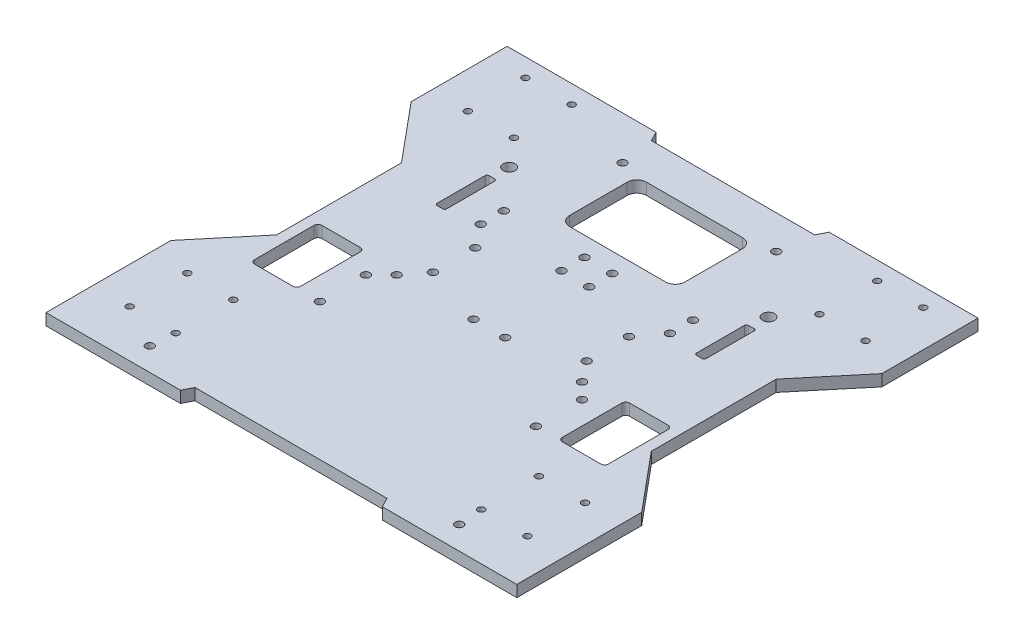
SolidWorks part; units mm, degrees
ref_plane "前视基准面" through (0, 0, 0) normal (0, 0, 1) x (1, 0, 0)
ref_plane "上视基准面" through (0, 0, 0) normal (0, 1, 0) x (1, 0, 0)
ref_plane "右视基准面" through (0, 0, 0) normal (1, 0, 0) x (0, 0, -1)
sketch "Sketch1" plane through (0, 0, 0) normal (0, 1, 0) x (1, 0, 0)
  line L0 (-122.5, 62.5) -> (-97.5, 32.5)
  line L1 (-122.5, 127.5) -> (-52.5, 127.5) construction
  line L2 (-122.5, 112.5) -> (-122.5, 62.5)
  line L3 (-122.5, -127.5) -> (-52.5, -127.5)
  line L4 (122.5, 112.5) -> (122.5, 62.5)
  line L5 (0, -127.5) -> (0, 127.5) construction
  line L6 (-122.5, 0) -> (122.5, 0) construction
  line L7 (-97.5, 32.5) -> (-97.5, -32.5)
  line L8 (-45, 112.5) -> (-42.5, 107.5)
  line L9 (-42.5, 107.5) -> (42.5, 107.5)
  line L10 (97.5, 32.5) -> (97.5, -32.5)
  line L11 (122.5, 62.5) -> (97.5, 32.5)
  line L12 (45, 112.5) -> (42.5, 107.5)
  line L13 (-122.5, -62.5) -> (-97.5, -32.5)
  line L14 (122.5, -62.5) -> (97.5, -32.5)
  line L15 (52.5, -127.5) -> (50, -122.5)
  line L16 (-42.5, -107.5) -> (0, -107.5) construction
  line L17 (-52.5, -127.5) -> (-50, -122.5)
  line L18 (-52.5, 127.5) -> (0, 127.5) construction
  line L19 (52.5, 127.5) -> (122.5, 127.5) construction
  line L20 (0, 127.5) -> (52.5, 127.5) construction
  line L21 (122.5, 62.5) -> (122.5, 0) construction
  line L22 (122.5, -62.5) -> (122.5, -127.5)
  line L23 (122.5, 0) -> (122.5, -62.5) construction
  line L24 (0, -127.5) -> (52.5, -127.5) construction
  line L25 (52.5, -127.5) -> (122.5, -127.5)
  line L26 (-52.5, -127.5) -> (0, -127.5) construction
  line L27 (-122.5, 62.5) -> (-122.5, 0) construction
  line L28 (-122.5, -62.5) -> (-122.5, -127.5)
  line L29 (-122.5, 0) -> (-122.5, -62.5) construction
  line L30 (0, -107.5) -> (42.5, -107.5) construction
  line L32 (50, -122.5) -> (-50, -122.5)
  line L37 (0, -60) -> (0, -40) construction
  line L38 (25, -50) -> (-25, -50) construction
  line L39 (50, -122.5) -> (42.5, -107.5) construction
  line L40 (-50, -122.5) -> (-42.5, -107.5) construction
  line L44 (122.5, 112.5) -> (45, 112.5)
  line L45 (122.5, 127.5) -> (122.5, 112.5) construction
  line L46 (52.5, 127.5) -> (45, 112.5) construction
  line L47 (45, 112.5) -> (0, 112.5) construction
  line L48 (-45, 112.5) -> (-122.5, 112.5)
  line L49 (0, 112.5) -> (-45, 112.5) construction
  line L50 (-122.5, 127.5) -> (-122.5, 112.5) construction
  line L51 (-52.5, 127.5) -> (-45, 112.5) construction
  point P0 (0, 0)
  point P15 (0, 107.5)
  point P17 (-97.5, 0)
  point P18 (97.5, 0)
  point P24 (0, -50)
  point P31 (-25, -60)
  point P37 (25, -40)
  point P40 (25, -60)
  dimension "D3" = 70
  dimension "D4" = 20
  dimension "D12" = 5
  dimension "D1" = 245
  dimension "D2" = 255
  dimension "D5" = 10
  dimension "D6" = 65
  dimension "D7" = 30
  dimension "D8" = 25
  dimension "D9" = 20
  dimension "D10" = 50
  dimension "D11" = 50
  dimension "D13" = 15
extrude "Boss-Extrude1" add sketch "Sketch1" along normal blind 6
sketch "Sketch4" plane through (0, 6, 0) normal (0, 1, 0) x (1, 0, 0)
  line L4 (-122.5, 112.5) -> (-122.5, 62.5) construction
  line B0 (-74.5, 108) -> (-108.5, 108)
  line B1 (-108.5, 108) -> (-108.5, 68)
  line B2 (-108.5, 68) -> (-74.5, 68)
  line B3 (-71.5, 71) -> (-71.5, 105)
  arc B4 (-71.5, 105) -> (-74.5, 108) centre (-74.5, 105) ccw
  arc B5 (-74.5, 68) -> (-71.5, 71) centre (-74.5, 71) ccw
  circle B6 centre (-103.5, 103) radius 1.75
  circle B7 centre (-103.5, 73) radius 1.75
  circle B8 centre (-79.5, 73) radius 1.75
  circle B9 centre (-79.5, 103) radius 1.75
  dimension "D1" = 14
  dimension "D2" = 5.5
sketch_block_instance "Block3-1"
sketch_block "Block3" parameters "D1"=3.5
extrude "Cut-Extrude3" cut sketch "Sketch4" against normal up to next contours B6 | B8 | B9 | B7
mirror "Mirror1" about plane through (0, 0, 0) normal (0, 0, 1) of "Cut-Extrude3"
mirror "Mirror2" about plane through (0, 0, 0) normal (1, 0, 0) of "Mirror1", "Cut-Extrude3"
sketch "Sketch14" plane through (0, 6, 0) normal (0, 1, 0) x (1, 0, 0)
  line L0 (-122.5, -62.5) -> (-122.5, -127.5) construction
  line L1 (122.5, -127.5) -> (122.5, -62.5) construction
  line L2 (-122.5, -127.5) -> (-52.5, -127.5) construction
  line L3 (52.5, -127.5) -> (122.5, -127.5) construction
  circle A1 centre (80.5, -115.5) radius 2.1
  circle A3 centre (-80.5, -115.5) radius 2.1
  dimension "D3" = 4.2
  dimension "D1" = 42
  dimension "D2" = 42
  dimension "D4" = 12
  dimension "D5" = 12
extrude "Cut-Extrude9" cut sketch "Sketch14" against normal up to next
sketch "Sketch16" plane through (0, 0, 0) normal (0, -1, 0) x (1, 0, 0)
  line L0 (40, -30) -> (40, -90) construction
  line L1 (40, -30) -> (-40, -30) construction
  line L2 (40, -30) -> (40, 30) construction
  line L3 (40, 30) -> (-40, 30) construction
  line L4 (-40, -30) -> (-40, 30) construction
  line L5 (0, 30) -> (0, -30) construction
  line L6 (40, 0) -> (-40, 0) construction
  line L7 (-40, -30) -> (-40, -90) construction
  circle A0 centre (40, 30) radius 2.1 construction
  circle A3 centre (40, -90) radius 2.1
  circle A4 centre (-40, -90) radius 2.1
  circle A11 centre (40, -13.3585) radius 2.1
  circle A12 centre (40, 8.6748) radius 2.1
  circle A13 centre (-40, 8.6748) radius 2.1
  circle A14 centre (-40, -13.3585) radius 2.1
  point P0 (0, 0)
  dimension "D4" = 4.2
  dimension "D1" = 60
  dimension "D2" = 80
  dimension "D3" = 60
extrude "Cut-Extrude12" cut sketch "Sketch16" against normal up to next
sketch "Sketch15" plane through (0, 6, 0) normal (0, 1, 0) x (1, 0, 0)
  line L8 (0, -2.75) -> (0, 2.75) construction
  line L9 (42.5, 107.5) -> (-42.5, 107.5) construction
  line L12 (-45, 112.5) -> (-122.5, 112.5) construction
  point P0 (-67.491, 22.5)
  point P30 (63.897, -115.6149)
  point P38 (63.897, -88.6149)
  line B0 (68.9826, 22.499) -> (65.9994, 22.501)
  line B1 (65, 23.501) -> (65, 48.501)
  line B2 (69.9994, 48.4984) -> (69.9832, 23.4984)
  line B3 (66.0006, 49.501) -> (69, 49.499)
  arc B4 (65.9994, 22.501) -> (65, 23.501) centre (66, 23.501) cw
  circle B5 centre (67.5058, 58.5) radius 3.1
  arc B6 (68.9826, 22.499) -> (69.9832, 23.4984) centre (68.9832, 23.499) ccw
  arc B7 (69, 49.499) -> (69.9994, 48.4984) centre (68.9994, 48.499) cw
  arc B8 (65, 48.501) -> (66.0006, 49.501) centre (66, 48.501) cw
  line B9 (-68.9826, 22.499) -> (-65.9994, 22.501)
  line B10 (-65, 23.501) -> (-65, 48.501)
  line B11 (-69.9994, 48.4984) -> (-69.9832, 23.4984)
  line B12 (-66.0006, 49.501) -> (-69, 49.499)
  arc B13 (-65.9994, 22.501) -> (-65, 23.501) centre (-66, 23.501) ccw
  circle B14 centre (-67.5058, 58.5) radius 3.1
  arc B15 (-68.9826, 22.499) -> (-69.9832, 23.4984) centre (-68.9832, 23.499) cw
  arc B16 (-69, 49.499) -> (-69.9994, 48.4984) centre (-68.9994, 48.499) ccw
  arc B17 (-65, 48.501) -> (-66.0006, 49.501) centre (-66, 48.501) ccw
  dimension "D2" = 90
  dimension "D1" = 130
sketch_block_instance "Block4-1"
sketch_block "Block4" parameters "D1"=1, "D2"=1, "D3"=5.1
sketch_block_instance "Block4-2"
extrude "Cut-Extrude11" cut sketch "Sketch15" against normal up to next
sketch "Sketch19" plane through (0, 6, 0) normal (0, 1, 0) x (1, 0, 0)
  circle A8 centre (-49.2275, 25.4525) radius 2.1
  circle A9 centre (-49.2275, 37.4525) radius 2.1
  circle A10 centre (-7.2275, 37.4525) radius 2.1
  circle A11 centre (-7.2275, 25.4525) radius 2.1
  circle A12 centre (7.2275, 25.4525) radius 2.1
  circle A13 centre (7.2275, 37.4525) radius 2.1
  circle A14 centre (49.2275, 37.4525) radius 2.1
  circle A15 centre (49.2275, 25.4525) radius 2.1
  dimension "D1" = 4.2
extrude "Cut-Extrude14" cut sketch "Sketch19" against normal up to next
sketch "Sketch20" plane through (0, 6, 0) normal (0, 1, 0) x (1, 0, 0)
  line L0 (0, -2.75) -> (0, 2.75) construction
  circle A4 centre (-56.2275, -51.3) radius 2.1
  circle A5 centre (-56.2275, -27.3) radius 2.1
  circle A6 centre (-48.2275, -19.3) radius 2.1
  circle A7 centre (-8.2275, -19.3) radius 2.1
  circle A8 centre (8.2275, -19.3) radius 2.1
  circle A9 centre (48.2275, -19.3) radius 2.1
  circle A10 centre (56.2275, -27.3) radius 2.1
  circle A11 centre (56.2275, -51.3) radius 2.1
  dimension "D1" = 4.2
extrude "Cut-Extrude15" cut sketch "Sketch20" against normal up to next
sketch "Sketch17" plane through (0, 6, 0) normal (0, 1, 0) x (1, 0, 0)
  line L0 (-0.0428, 10.3282) -> (-0.0428, 91.3341) construction
  line L1 (42.5, 107.5) -> (-42.5, 107.5) construction
  line L2 (-25.0428, 87.5) -> (24.9572, 87.5)
  line L3 (-30.0428, 82.5) -> (-30.0428, 52.5)
  line L4 (-25.0428, 47.5) -> (24.9572, 47.5)
  line L5 (29.9572, 82.5) -> (29.9572, 52.5)
  line L6 (-0.0428, 2.8282) -> (-0.0428, 87.5) construction
  line L7 (-30.0428, 67.5) -> (29.9572, 67.5) construction
  line L8 (0, -2.75) -> (0, 2.75) construction
  line L9 (-90.0796, -16.4007) -> (-70.0796, -16.4007)
  line L10 (-92.0796, -18.4007) -> (-92.0796, -49.4007)
  line L11 (-90.0796, -51.4007) -> (-70.0796, -51.4007)
  line L12 (-68.0796, -18.4007) -> (-68.0796, -49.4007)
  line L13 (68.0796, -18.4007) -> (68.0796, -49.4007)
  line L14 (90.0796, -51.4007) -> (70.0796, -51.4007)
  line L15 (92.0796, -18.4007) -> (92.0796, -49.4007)
  line L16 (90.0796, -16.4007) -> (70.0796, -16.4007)
  arc A0 (-25.0428, 87.5) -> (-30.0428, 82.5) centre (-25.0428, 82.5) ccw
  arc A1 (-30.0428, 52.5) -> (-25.0428, 47.5) centre (-25.0428, 52.5) ccw
  arc A2 (24.9572, 47.5) -> (29.9572, 52.5) centre (24.9572, 52.5) ccw
  arc A3 (24.9572, 87.5) -> (29.9572, 82.5) centre (24.9572, 82.5) cw
  arc A4 (-70.0796, -51.4007) -> (-68.0796, -49.4007) centre (-70.0796, -49.4007) ccw
  arc A5 (-92.0796, -49.4007) -> (-90.0796, -51.4007) centre (-90.0796, -49.4007) ccw
  arc A6 (-70.0796, -16.4007) -> (-68.0796, -18.4007) centre (-70.0796, -18.4007) cw
  arc A7 (-90.0796, -16.4007) -> (-92.0796, -18.4007) centre (-90.0796, -18.4007) ccw
  arc A8 (90.0796, -16.4007) -> (92.0796, -18.4007) centre (90.0796, -18.4007) cw
  arc A9 (70.0796, -16.4007) -> (68.0796, -18.4007) centre (70.0796, -18.4007) ccw
  arc A10 (92.0796, -49.4007) -> (90.0796, -51.4007) centre (90.0796, -49.4007) cw
  arc A11 (70.0796, -51.4007) -> (68.0796, -49.4007) centre (70.0796, -49.4007) cw
  point P2 (-0.0428, 67.5)
  point P12 (-30.0428, 87.5)
  point P17 (29.9572, 47.5)
  point P20 (29.9572, 87.5)
  point P28 (-92.0796, -51.4007)
  point P31 (-68.0796, -16.4007)
  point P34 (-92.0796, -16.4007)
  point P49 (92.0796, -16.4007)
  point P50 (68.0796, -16.4007)
  point P51 (92.0796, -51.4007)
  dimension "D3" = 5
  dimension "D7" = 2
  dimension "D1" = 60
  dimension "D2" = 40
  dimension "D4" = 20
  dimension "D5" = 24
  dimension "D6" = 35
extrude "Cut-Extrude13" cut sketch "Sketch17" against normal up to next and the other way through all
equation "\"D5@Sketch14\"=\"D4@Sketch14\""
